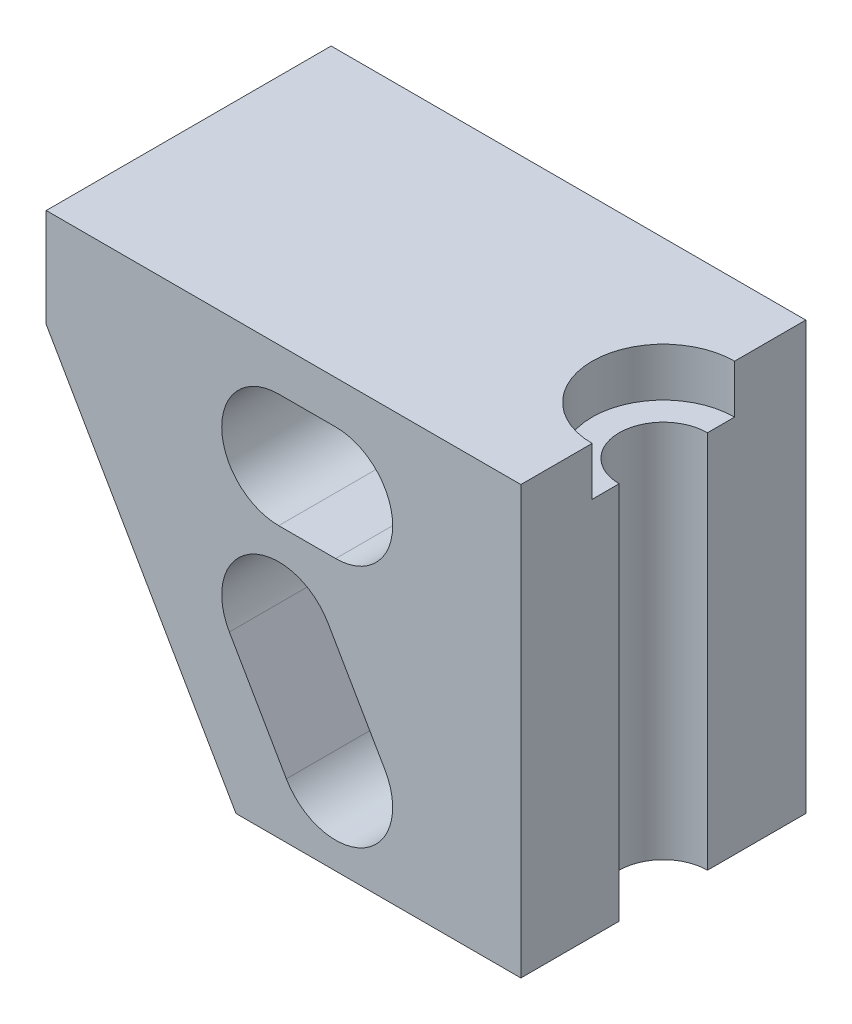
SolidWorks part; units mm, degrees
ref_plane "정면" through (0, 0, 0) normal (0, 0, 1) x (1, 0, 0)
ref_plane "윗면" through (0, 0, 0) normal (0, 1, 0) x (1, 0, 0)
ref_plane "우측면" through (0, 0, 0) normal (1, 0, 0) x (0, 0, -1)
sketch "스케치1" plane through (0, 0, 0) normal (0, 0, 1) x (1, 0, 0)
  line L0 (0, 0) -> (0, 15)
  line L1 (0, 15) -> (-18.6603, 15)
  line L4 (-18.6603, 15) -> (-10, 0)
  line L5 (-10, 0) -> (0, 0)
  line L6 (-6.7679, 7.4019) -> (-4.7679, 3.9378)
  line L7 (-10.2321, 5.4019) -> (-8.2321, 1.9378)
  line L8 (-8.5, 13.5) -> (-6.5, 13.5)
  line L9 (-6.5, 9.5) -> (-8.5, 9.5)
  circle A0 centre (-6.5, 2.9378) radius 2
  circle A1 centre (-8.5, 6.4019) radius 2
  circle A2 centre (-8.5, 11.5) radius 2
  circle A3 centre (-6.5, 11.5) radius 2
  dimension "D4" = 4
  dimension "D8" = 4
  dimension "D1" = 15
  dimension "D2" = 60
  dimension "D3" = 10
  dimension "D5" = 2
  dimension "D6" = 2.5
  dimension "D7" = 6.5
  dimension "D9" = 2
  dimension "D11" = 1.5
extrude "보스-돌출1" add sketch "스케치1" along normal blind 10 contours L4 L5 L0 L1 A3 L9 A2 L8 A1 L6 A0 L7
sketch "스케치2" plane through (0, 0, 0) normal (0, -1, 0) x (1, 0, 0)
  line L0 (0, 10) -> (0, 0) construction
  circle A0 centre (0, 5) radius 1.55
  dimension "D1" = 3.1
extrude "컷-돌출1" cut sketch "스케치2" against normal through all
sketch "스케치3" plane through (0, 15, 0) normal (0, 1, 0) x (1, 0, 0)
  circle A0 centre (0, -5) radius 2.5
  dimension "D1" = 5
extrude "컷-돌출2" cut sketch "스케치3" against normal blind 1.7
ref_plane "평면2" through (-10, 0, 10) normal (0.5, -0.866, 0) x (-0.866, -0.5, 0)
sketch "스케치4" plane through (0, 0, 10) normal (0, 0, 1) x (1, 0, 0)
  line L0 (-18.6603, 15) -> (-16.6603, 15)
  line L1 (0, 15) -> (-18.6603, 15) construction
  line L2 (-16.6603, 15) -> (-16.6603, 11.5359)
  line L3 (-18.6603, 15) -> (-10, 0) construction
  line L4 (-16.6603, 11.5359) -> (-18.6603, 15)
  dimension "D1" = 2
extrude "컷-돌출3" cut sketch "스케치4" against normal through all
